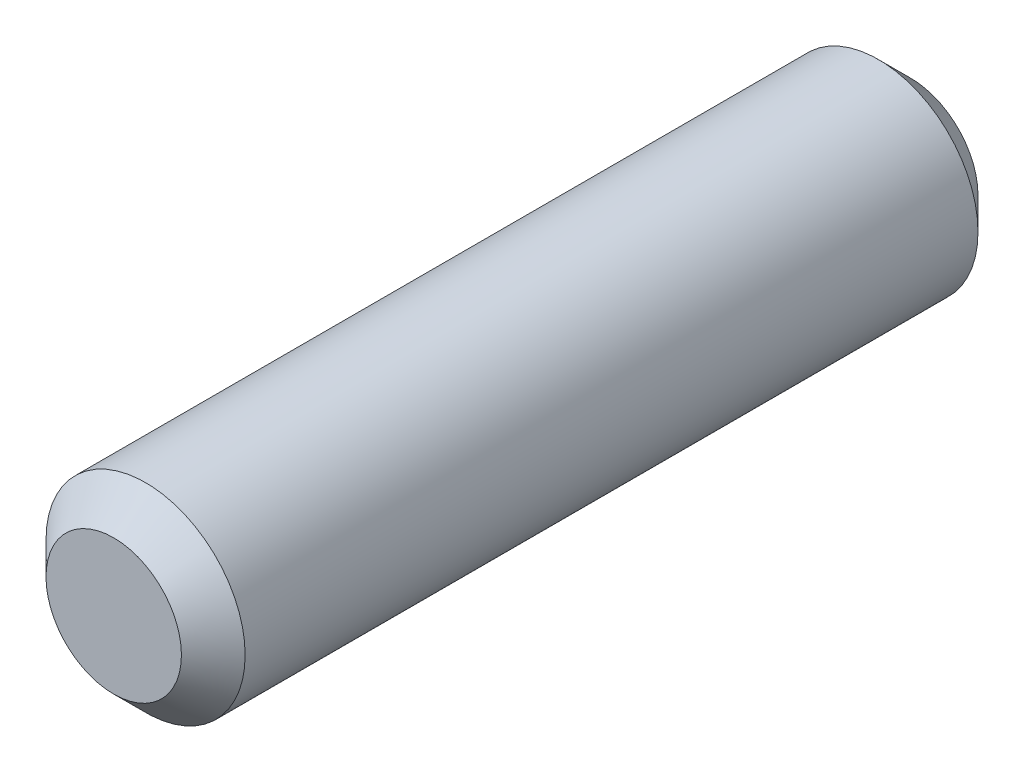
SolidWorks part; units mm, degrees
ref_plane "Front Plane" through (0, 0, 0) normal (0, 0, 1) x (1, 0, 0)
ref_plane "Top Plane" through (0, 0, 0) normal (0, 1, 0) x (1, 0, 0)
ref_plane "Right Plane" through (0, 0, 0) normal (1, 0, 0) x (0, 0, -1)
sketch "Sketch1" plane through (0, 0, 0) normal (0, 0, 1) x (1, 0, 0)
  circle A0 centre (0, 0) radius 1.1906
  dimension "D1" = 2.3813
extrude "Boss-Extrude1" add sketch "Sketch1" along normal mid plane 9.525
chamfer "Chamfer1" distance 0.381 2 edges at (1.1906, 0, -4.7625) (1.1906, 0, 4.7625)
